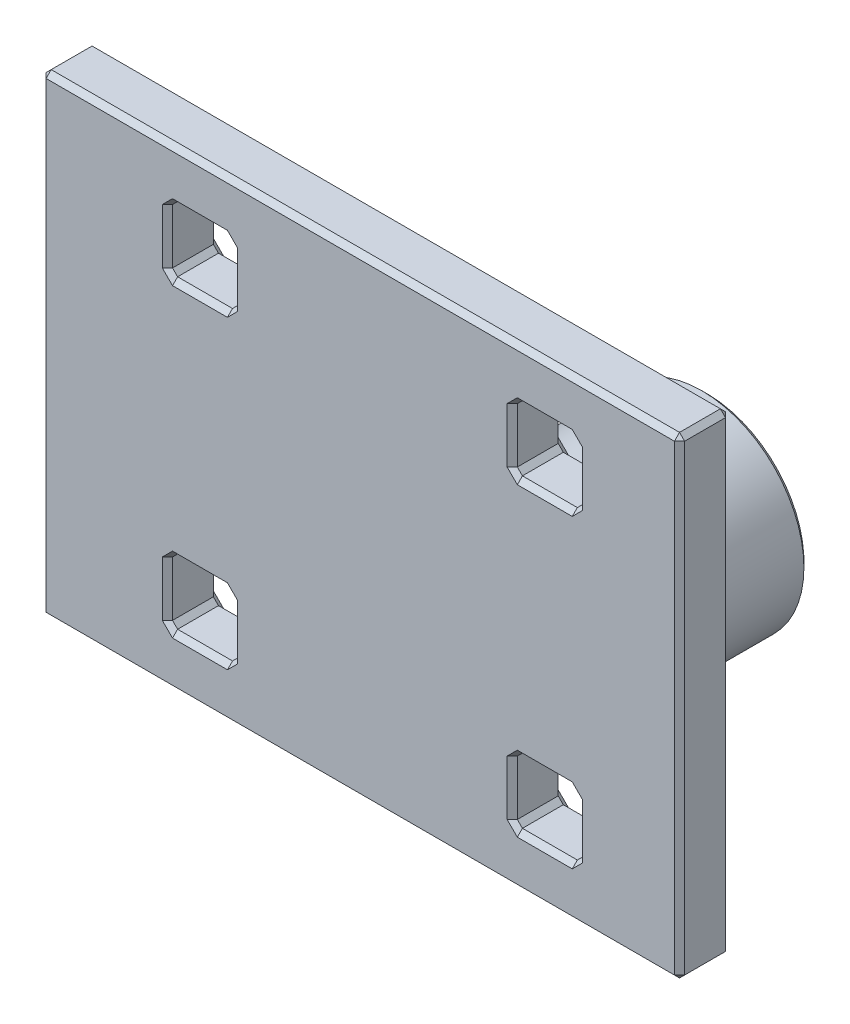
SolidWorks part; units mm, degrees
ref_plane "Ebene vorne" through (0, 0, 0) normal (0, 0, 1) x (1, 0, 0)
ref_plane "Ebene oben" through (0, 0, 0) normal (0, 1, 0) x (1, 0, 0)
ref_plane "Ebene rechts" through (0, 0, 0) normal (1, 0, 0) x (0, 0, -1)
sketch "Skizze1" plane through (0, 0, 0) normal (0, 0, 1) x (1, 0, 0)
  line L1 (-27.1752, 13.2787) -> (22.8248, 13.2787)
  line L2 (-27.1752, 13.2787) -> (-27.1752, -23.7213)
  line L3 (-27.1752, -23.7213) -> (22.8248, -23.7213)
  line L4 (22.8248, 13.2787) -> (22.8248, -23.7213)
  line L5 (-19.1752, 9.2787) -> (-14.0752, 9.2787)
  line L6 (-19.1752, 9.2787) -> (-19.1752, 4.1787)
  line L7 (-19.1752, 4.1787) -> (-14.0752, 4.1787)
  line L8 (-14.0752, 9.2787) -> (-14.0752, 4.1787)
  line L9 (7.8248, 9.2787) -> (12.9248, 9.2787)
  line L10 (7.8248, 9.2787) -> (7.8248, 4.1787)
  line L11 (7.8248, 4.1787) -> (12.9248, 4.1787)
  line L12 (12.9248, 9.2787) -> (12.9248, 4.1787)
  line L13 (-17.1664, -15.5325) -> (-12.0664, -15.5325)
  line L14 (-17.1664, -15.5325) -> (-17.1664, -20.6325)
  line L15 (-17.1664, -20.6325) -> (-12.0664, -20.6325)
  line L16 (-12.0664, -15.5325) -> (-12.0664, -20.6325)
  line L17 (9.8336, -15.5325) -> (14.9336, -15.5325)
  line L18 (9.8336, -15.5325) -> (9.8336, -20.6325)
  line L19 (9.8336, -20.6325) -> (14.9336, -20.6325)
  line L20 (14.9336, -15.5325) -> (14.9336, -20.6325)
  point P20 (-19.1752, 6.7287)
  dimension "D1" = 50
  dimension "D2" = 37
  dimension "D3" = 5.1
  dimension "D4" = 5.1
  dimension "D5" = 5.1
  dimension "D6" = 4
  dimension "D7" = 4
  dimension "D8" = 5.1
  dimension "D9" = 5.1
  dimension "D10" = 5.1
  dimension "D11" = 5.1
  dimension "D12" = 21.9
  dimension "D13" = 21.9
  dimension "D14" = 8
extrude "Aufsatz-Linear austragen1" add sketch "Skizze1" along normal blind 4 contours L2 L1 L4 L3
sketch "Skizze2" plane through (0, 0, 0) normal (0, 0, -1) x (-1, 0, 0)
  line L0 (12.1752, 9.2787) -> (17.2752, 9.2787)
  line L1 (-14.8248, 9.2787) -> (-9.7248, 9.2787)
  line L2 (-14.8248, 9.2787) -> (-14.8248, 4.1787)
  line L3 (-14.8248, 4.1787) -> (-9.7248, 4.1787)
  line L4 (-9.7248, 9.2787) -> (-9.7248, 4.1787)
  line L17 (12.1752, 9.2787) -> (12.1752, 4.1787)
  line L18 (12.1752, 4.1787) -> (17.2752, 4.1787)
  line L19 (17.2752, 9.2787) -> (17.2752, 4.1787)
  line L20 (-14.8248, -14.6213) -> (-9.7248, -14.6213)
  line L21 (-14.8248, -14.6213) -> (-14.8248, -19.7213)
  line L22 (-14.8248, -19.7213) -> (-9.7248, -19.7213)
  line L23 (-9.7248, -14.6213) -> (-9.7248, -19.7213)
  line L24 (12.1752, -14.6213) -> (17.2752, -14.6213)
  line L25 (12.1752, -14.6213) -> (12.1752, -19.7213)
  line L26 (12.1752, -19.7213) -> (17.2752, -19.7213)
  line L27 (17.2752, -14.6213) -> (17.2752, -19.7213)
  line L28 (27.1752, 13.2787) -> (-22.8248, 13.2787) construction
  line L29 (-22.8248, 13.2787) -> (-22.8248, -23.7213) construction
  line L30 (27.1752, -23.7213) -> (-22.8248, -23.7213) construction
  dimension "D1" = 5.1
  dimension "D2" = 5.1
  dimension "D3" = 4
  dimension "D4" = 4
  dimension "D5" = 8
  dimension "D6" = 21.9
  dimension "D7" = 8
  dimension "D8" = 4
  dimension "D9" = 5.1
  dimension "D10" = 5.1
  dimension "D11" = 4
  dimension "D12" = 5.1
  dimension "D13" = 5.1
  dimension "D14" = 21.9
extrude "Schnitt-Linear austragen1" cut sketch "Skizze2" against normal through all
sketch "Skizze3" plane through (0, 0, 0) normal (0, 0, -1) x (-1, 0, 0)
  line L0 (-22.8248, -5.2213) -> (27.1752, -5.2213) construction
  line L1 (-22.8248, 13.2787) -> (-22.8248, -23.7213) construction
  line L2 (27.1752, 13.2787) -> (27.1752, -23.7213) construction
  circle A0 centre (-9.9653, -5.2213) radius 8
  circle A1 centre (-9.9653, -5.2213) radius 5.061
extrude "Aufsatz-Linear austragen2" add sketch "Skizze3" along normal blind 11
chamfer "Fase1" distance 0.4 angle 45 64 edges at (4.9044, -5.2213, -11) (1.9653, -5.2213, 0) (1.9653, -5.2213, -11) (-12.1752, -14.6213, 2) (-17.2752, -14.6213, 2) (-17.2752, -19.7213, 2) (-14.7252, -14.6213, 4) (-17.2752, -17.1713, 4) (-14.7252, -19.7213, 4) (-12.1752, -17.1713, 4) (-12.1752, -19.7213, 2) (-14.7252, -14.6213, 0) (-17.2752, -17.1713, 0) (-14.7252, -19.7213, 0) (-12.1752, -17.1713, 0) (14.8248, -14.6213, 2) (9.7248, -14.6213, 2) (9.7248, -19.7213, 2) (12.2748, -14.6213, 4) (9.7248, -17.1713, 4) (12.2748, -19.7213, 4) (14.8248, -17.1713, 4) (14.8248, -19.7213, 2) (12.2748, -14.6213, 0) (9.7248, -17.1713, 0) (12.2748, -19.7213, 0) (14.8248, -17.1713, 0) (-12.1752, 9.2787, 2) (-17.2752, 9.2787, 2) (-17.2752, 4.1787, 2) (-14.7252, 9.2787, 4) (-17.2752, 6.7287, 4) (-14.7252, 4.1787, 4) (-12.1752, 6.7287, 4) (-12.1752, 4.1787, 2) (-14.7252, 9.2787, 0) (-17.2752, 6.7287, 0) (-14.7252, 4.1787, 0) (-12.1752, 6.7287, 0) (14.8248, 6.7287, 0) (12.2748, 4.1787, 0) (9.7248, 6.7287, 0) (12.2748, 9.2787, 0) (14.8248, 6.7287, 4) (14.8248, 4.1787, 2) (12.2748, 4.1787, 4) (9.7248, 4.1787, 2) (9.7248, 6.7287, 4) (9.7248, 9.2787, 2) (12.2748, 9.2787, 4) (14.8248, 9.2787, 2) (-2.1752, -23.7213, 0) (22.8248, -5.2213, 0) (-2.1752, 13.2787, 0) (-27.1752, -5.2213, 0) (-2.1752, -23.7213, 4) (-27.1752, -23.7213, 2) (-27.1752, -5.2213, 4) (-27.1752, 13.2787, 2) (-2.1752, 13.2787, 4) (22.8248, 13.2787, 2) (22.8248, -5.2213, 4) (22.8248, -23.7213, 2) (4.9044, -5.2213, 0)
sketch "Skizze4" plane through (0, 0, 0) normal (0, 1, 0) x (1, 0, 0)
  line L0 (1.9388, 5) -> (33.8077, 5) construction
  line L1 (9.9653, 15.4329) -> (9.9653, -5.5067) construction
  line L2 (1.9653, 10.6) -> (1.9653, 0.4) construction
  line L3 (17.5653, 11) -> (2.3653, 11) construction
  circle A1 centre (9.9653, 4.9631) radius 1.2656
  dimension "D1" = 8
  dimension "D2" = 6
extrude "Schnitt-Linear austragen2" cut sketch "Skizze4" against normal mid plane 200
